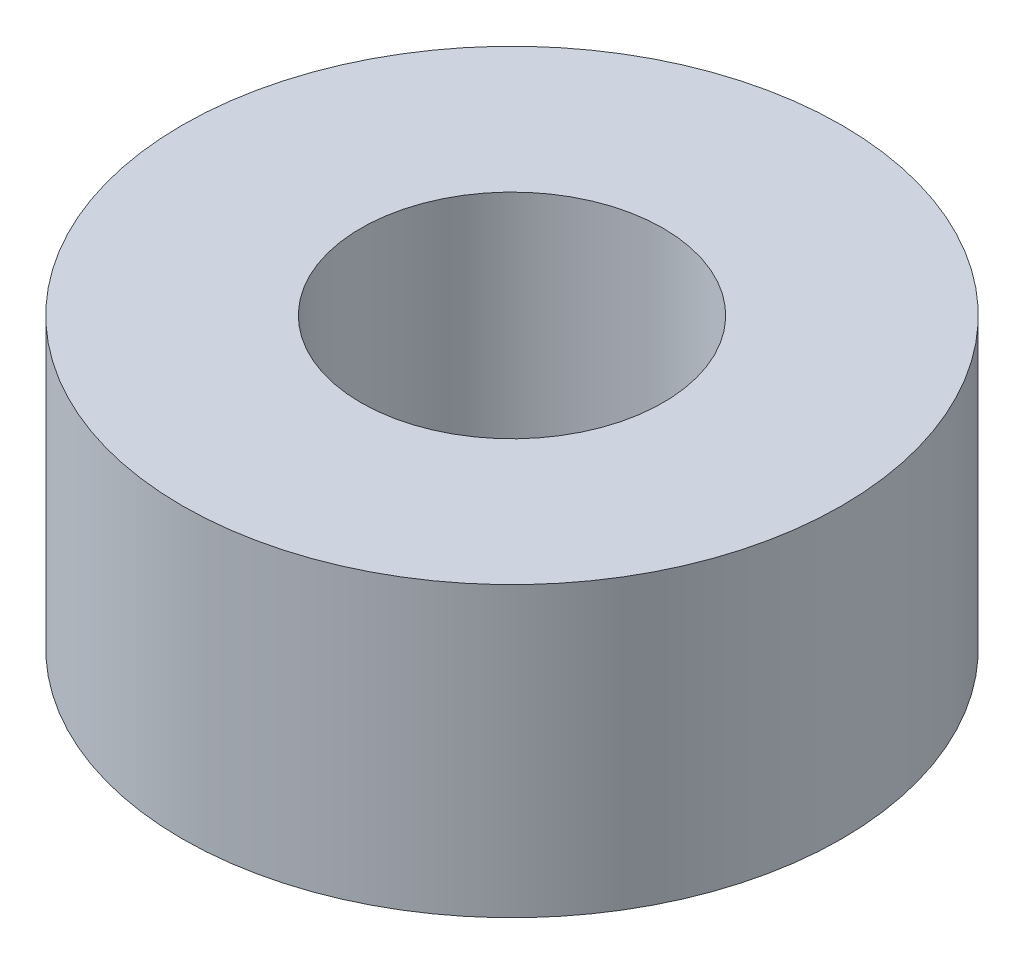
SolidWorks part; units mm, degrees
ref_plane "Front Plane" through (0, 0, 0) normal (0, 0, 1) x (1, 0, 0)
ref_plane "Top Plane" through (0, 0, 0) normal (0, 1, 0) x (1, 0, 0)
ref_plane "Right Plane" through (0, 0, 0) normal (1, 0, 0) x (0, 0, -1)
sketch "Sketch1" plane through (0, 0, 0) normal (0, 1, 0) x (1, 0, 0)
  circle A0 centre (0, 0) radius 5.5
  circle A1 centre (0, 0) radius 12
extrude "Boss-Extrude2" add sketch "Sketch1" along normal blind 10.5
